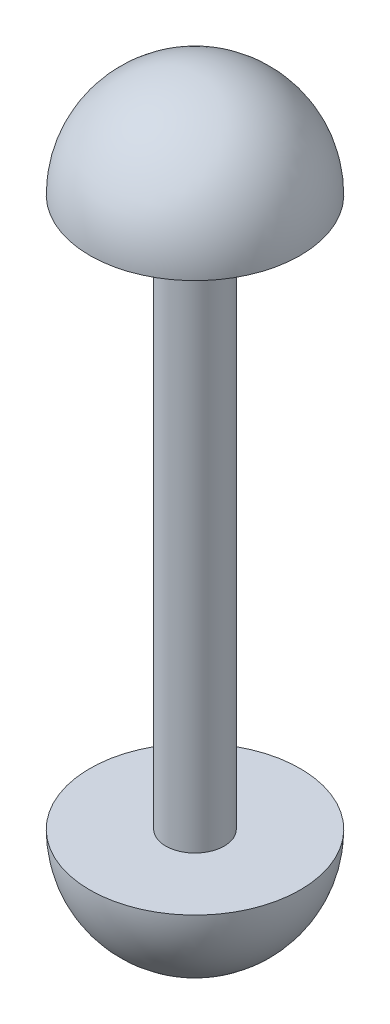
SolidWorks part; units mm, degrees
ref_plane "Front Plane" through (0, 0, 0) normal (0, 0, 1) x (1, 0, 0)
ref_plane "Top Plane" through (0, 0, 0) normal (0, 1, 0) x (1, 0, 0)
ref_plane "Right Plane" through (0, 0, 0) normal (1, 0, 0) x (0, 0, -1)
sketch "Sketch1" plane through (0, 0, 0) normal (0, 0, 1) x (1, 0, 0)
  line L0 (-18, 0) -> (-5, 0)
  line L1 (-5, 0) -> (-5, -94)
  line L2 (0, 18) -> (0, -112)
  line L4 (-18, -94) -> (-5, -94)
  arc A0 (0, 18) -> (-18, 0) centre (0, 0) ccw
  arc A1 (0, -112) -> (-18, -94) centre (0, -94) cw
  dimension "D1" = 36
  dimension "D2" = 5
revolve "Revolve1" add sketch "Sketch1" angle 360 about L2
